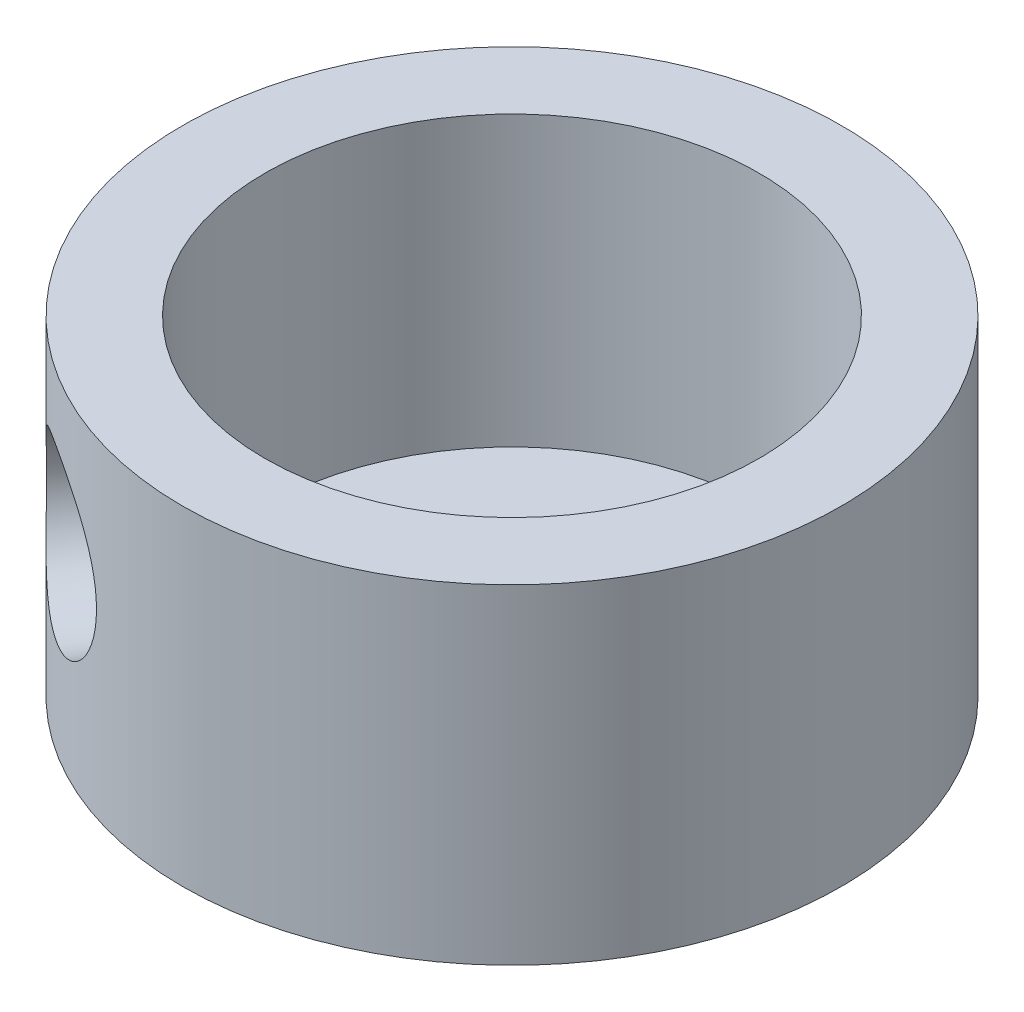
SolidWorks part; units mm, degrees
ref_plane "前基準面" through (0, 0, 0) normal (0, 0, 1) x (1, 0, 0)
ref_plane "上基準面" through (0, 0, 0) normal (0, 1, 0) x (1, 0, 0)
ref_plane "右基準面" through (0, 0, 0) normal (1, 0, 0) x (0, 0, -1)
sketch "草圖1" plane through (0, 0, 0) normal (0, 1, 0) x (1, 0, 0)
  circle A0 centre (0, 0) radius 40
  dimension "D1" = 80
extrude "填料-伸長1" add sketch "草圖1" along normal blind 40
sketch "草圖3" plane through (0, 40, 0) normal (0, 1, 0) x (1, 0, 0)
  circle A0 centre (0, 0) radius 30
  circle A1 centre (0, 0) radius 40 construction
  dimension "D1" = 10
extrude "除料-伸長2" cut sketch "草圖3" against normal blind 35
hole_wizard "Ø20.5 (20.5) 直徑孔1" positions "3D草圖1" profile "草圖4" hole size "Ø20.5" standard "JIS"
sketch3d "3D草圖1"
  point P0 (-21.7448, 21.9418, 33.5733)
sketch "草圖4" plane through (-21.7448, 21.9418, 33.5733) normal (0, 1, 0) x (0.8393, 0, 0.5436)
  line L0 (0, 0) -> (0, 10)
  line L1 (0, 10) -> (10.25, 10)
  line L2 (10.25, 10) -> (10.25, 0)
  line L5 (10.25, 0) -> (0, 0)
  line L11 (0, -6.35) -> (0, 107.95) construction
  dimension "貫穿孔直徑" = 20.5
  dimension "貫穿孔深度" = 10
